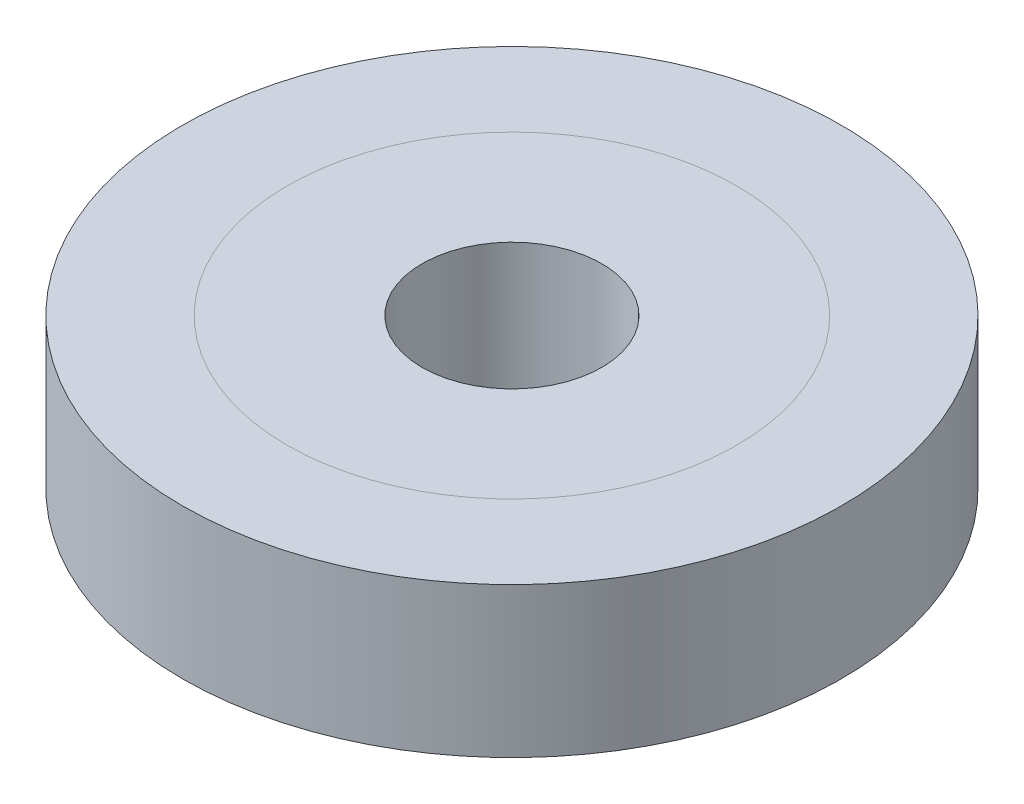
SolidWorks part; units mm, degrees
ref_plane "前视基准面" through (0, 0, 0) normal (0, 0, 1) x (1, 0, 0)
ref_plane "上视基准面" through (0, 0, 0) normal (0, 1, 0) x (1, 0, 0)
ref_plane "右视基准面" through (0, 0, 0) normal (1, 0, 0) x (0, 0, -1)
sketch "草图1" plane through (0, 0, 0) normal (0, 1, 0) x (1, 0, 0)
  circle A0 centre (0, 0) radius 3
  circle A1 centre (0, 0) radius 7.5
  dimension "D1" = 6
  dimension "D2" = 15
extrude "凸台-拉伸1" add sketch "草图1" along normal mid plane 5
sketch "草图2" plane through (0, 0, 0) normal (0, 1, 0) x (1, 0, 0)
  circle A0 centre (0, 0) radius 11
  circle A1 centre (0, 0) radius 7.5 construction
  circle A2 centre (0, 0) radius 7.5
  dimension "D1" = 22
extrude "凸台-拉伸2" add sketch "草图2" along normal mid plane 5 separate body
sketch "草图3" plane through (0, 2.5, 0) normal (0, 1, 0) x (1, 0, 0)
  circle A2 centre (0, 0) radius 10.5
  circle A3 centre (0, 0) radius 10.5 construction
  text T0 "https://item.taobao.com/item.htm?spm=a1z10.3-c.w4002-15226105362.15.e702319dne47Ao&id=538767949710" font "黑体" height 0.5
  dimension "D1" = 0.5
extrude "切除-拉伸1" [suppressed] cut sketch "草图3" against normal blind 0.1
